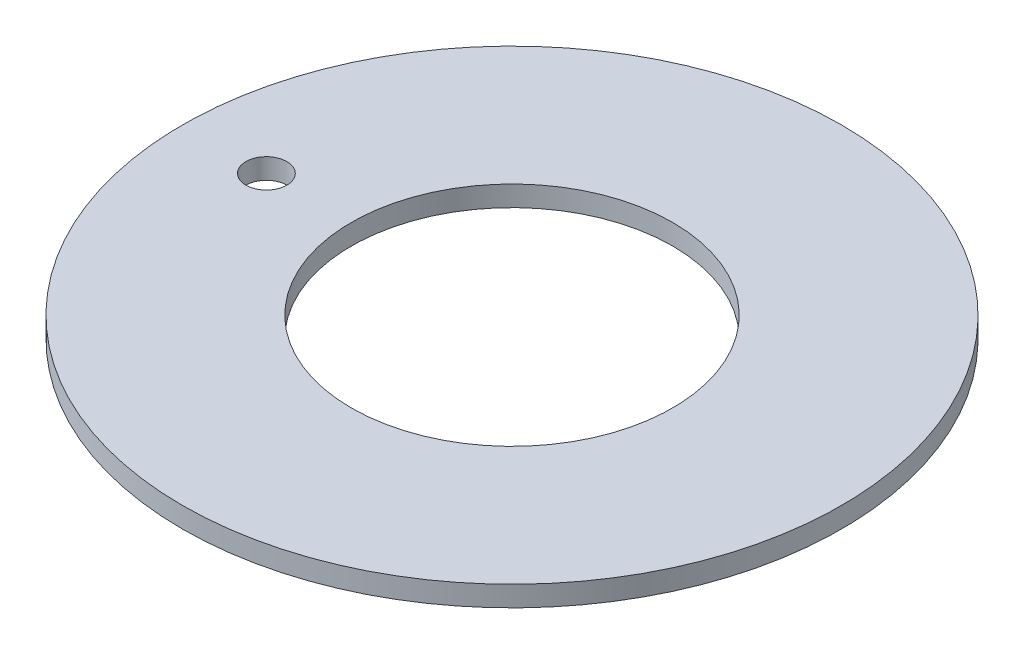
SolidWorks part; units mm, degrees
ref_plane "Front Plane" through (0, 0, 0) normal (0, 0, 1) x (1, 0, 0)
ref_plane "Top Plane" through (0, 0, 0) normal (0, 1, 0) x (1, 0, 0)
ref_plane "Right Plane" through (0, 0, 0) normal (1, 0, 0) x (0, 0, -1)
sketch "Sketch1" plane through (0, 0, 0) normal (0, 1, 0) x (1, 0, 0)
  circle A0 centre (0, 0) radius 15.7
  circle A1 centre (0, 0) radius 32.2
  dimension "D1" = 31.4
  dimension "D2" = 64.4
extrude "Boss-Extrude1" add sketch "Sketch1" along normal blind 2
sketch "Sketch2" plane through (0, 2, 0) normal (0, 1, 0) x (1, 0, 0)
  circle A0 centre (0, 0) radius 24 construction
  circle A3 centre (-24, 0) radius 2
  dimension "D1" = 48
  dimension "D2" = 4
extrude "Cut-Extrude1" cut sketch "Sketch2" against normal through all
